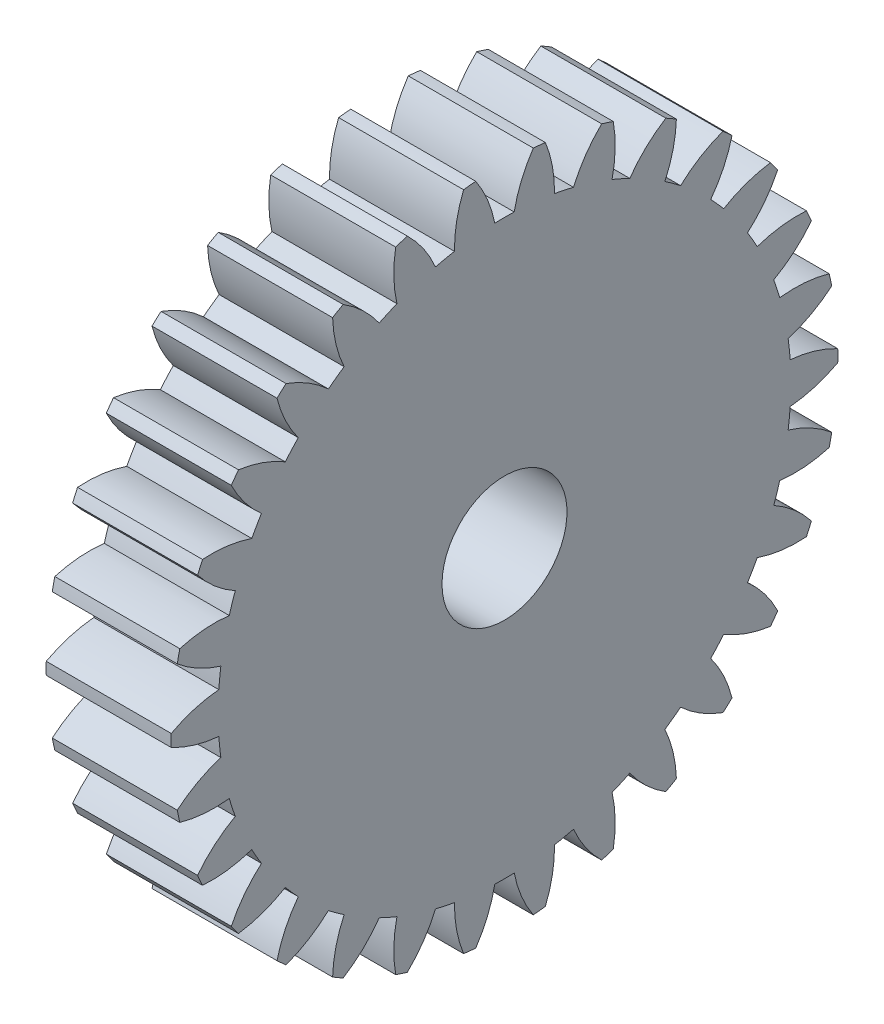
SolidWorks part; units mm, degrees
ref_plane "Plane1" through (0, 0, 0) normal (0, 0, 1) x (1, 0, 0)
ref_plane "Plane2" through (0, 0, 0) normal (0, 1, 0) x (1, 0, 0)
ref_plane "Plane3" through (0, 0, 0) normal (1, 0, 0) x (0, 0, -1)
sketch "HoldingSke" plane through (0, 0, 0) normal (0, 1, 0) x (1, 0, 0)
  line L0 (0, 0) -> (1.7321, -1)
  line L1 (-15, 0) -> (100, 0) construction
  line L2 (0, 0) -> (-2.1039, 2.3779)
  line L3 (0, 0) -> (-11.863, 4.5341)
  line L4 (0, 0) -> (7.479, 4.318)
  line L5 (0, 0) -> (-46.8476, -17.4728)
  line L6 (0, 0) -> (-2.4869, -1.6779)
  line L7 (-2.1039, 2.3779) -> (8.6586, 51.2059)
  line L8 (-76.2, 54.61) -> (-75.7, 54.61)
  line L9 (-71.009, 38.7566) -> (-53.1078, 45.2721)
  line L10 (-76.2, 71.12) -> (104.1128, 71.12)
  line L11 (0, 0) -> (-3, 0)
  line L12 (-76.2, 101.6) -> (-76.181, 101.6)
  line L13 (24.9733, 27.94) -> (52.9518, 28.4284)
  line L14 (24.9733, 27.94) -> (24.9743, 27.94)
  line L15 (24.9733, 27.94) -> (100.4006, 29.5858)
  line L16 (-63.627, -0.5) -> (-12.827, -0.5)
  circle A0 centre (0, 0) radius 1.5
  circle A1 centre (0, 0) radius 6.874
  circle A2 centre (0, 0) radius 37.5
  circle A3 centre (0, 0) radius 1.5
  dimension "MHD" = 13.748
  dimension "Hub_dia" = 75
  dimension "Bore" = 3
  dimension "MBD" = 3
  dimension "Num_teeth" = 30
  dimension "Pitch" = 2
  dimension "Overall_len" = 50
  dimension "Show_teeth" = 30
  dimension "Thickness" = 3
  dimension "OAL" = 50.0001
  dimension "T_dim" = 0.5
  dimension "Ap" = 20
  dimension "H" = 19.05
  dimension "Pitch_radius" = 180.3128
  dimension "Width" = 3
  dimension "Backlash" = 0.019
  dimension "Addendum_fac" = 1
  dimension "Dedendum_fac" = 1.25
  dimension "Clearance_fac" = 0.25
  dimension "Dedendum_add" = 0.001
  dimension "Module" = 0.5
sketch "BasProSke" plane through (0, 0, 0) normal (0, 1, 0) x (1, 0, 0)
  line L0 (-10, 0) -> (60, 0) construction
  line L1 (0, 0) -> (0, 8)
  line L2 (0, 0) -> (3, 0)
  line L3 (3, 0) -> (3, 8)
  line L4 (3, 8) -> (0, 8)
  dimension "Thickness" = 3
  dimension "Diameter" = 16
revolve "Base-Revolve" add sketch "BasProSke" angle 360 about L0
sketch "TooCutSke" plane through (0, 0, 0) normal (1, 0, 0) x (0, 0, -1)
  line L1 (0, 0) -> (0, 107) construction
  line L2 (0, 0) -> (-0.4258, 7.4879) construction
  line L3 (0, 0) -> (-1.5661, 14.9007) construction
  line L4 (-0.4258, 7.4879) -> (-0.7831, 7.4504) construction
  arc A0 (0.2331, 6.87) -> (-0.2331, 6.87) centre (0, 0) ccw
  arc A1 (0.707, 7.9942) -> (-0.707, 7.9942) centre (0, 0) ccw
  circle A2 centre (0, 0) radius 7.5 construction
  circle A3 centre (0, 0) radius 7.0477 construction
  arc A4 (-0.2331, 6.87) -> (-0.707, 7.9942) centre (-3.1767, 6.2911) ccw
  arc A5 (0.707, 7.9942) -> (0.2331, 6.87) centre (3.1767, 6.2911) ccw
  dimension "Root_dia" = 13.748
  dimension "Overcut_dia" = 16.0508
  dimension "Pitch_dia" = 15
  dimension "Base_dia" = 14.0954
  dimension "Flank_rad" = 3
  dimension "Half_ang" = 6
  dimension "Half_CT" = 0.3593
extrude "ToothCut" cut sketch "TooCutSke" along normal through all
fillet "Breaks" [suppressed] radius 0.01
fillet "RootFillets" [suppressed] radius 0.126
pattern_circular "TeethCuts" count 30 every 12 about axis through (-10, 0, 0) along (1, 0, 0) of "ToothCut", "RootFillets", "Breaks"
sketch "HubNeaOneSke" plane through (0, 0, 0) normal (-1, 0, 0) x (0, 0, 1)
  circle A0 centre (0, 0) radius 6.874
  dimension "Diameter" = 13.748
extrude "HubNearOne" [suppressed] add sketch "HubNeaOneSke" along normal blind 47.0001
sketch "HubNeaBotSke" plane through (0, 0, 0) normal (-1, 0, 0) x (0, 0, 1)
  circle A0 centre (0, 0) radius 6.874
  dimension "Diameter" = 13.748
extrude "HubNearBoth" [suppressed] add sketch "HubNeaBotSke" along normal blind 23.5
ref_plane "FarPln" through (3, 0, 0) normal (1, 0, 0) x (0, 0, -1)
sketch "HubFarSke" plane through (3, 0, 0) normal (1, 0, 0) x (0, 0, -1)
  circle A0 centre (0, 0) radius 6.874
  dimension "Diameter" = 13.748
extrude "HubFar" [suppressed] add sketch "HubFarSke" along normal blind 23.5
sketch "BorSke" plane through (0, 0, 0) normal (1, 0, 0) x (0, 0, -1)
  circle A0 centre (0, 0) radius 1.5
  dimension "Diameter" = 3
extrude "Bore" cut sketch "BorSke" along normal mid plane 100.0001
sketch "KeySke" plane through (0, 0, 0) normal (1, 0, 0) x (0, 0, -1)
  line L0 (-0.6, 0) -> (-0.6, 2)
  line L1 (-0.6, 2) -> (0.6, 2)
  line L2 (0.6, 2) -> (0.6, 0)
  line L3 (0, 0) -> (0, 34) construction
  line L4 (-0.6, 0) -> (0.6, 0)
  dimension "Offset" = 2
  dimension "Width" = 1.2
extrude "Keyway" [suppressed] cut sketch "KeySke" along normal mid plane 100.0001
pattern_circular "Keyway2" [suppressed] count 2 every 90 about axis through (-10, 0, 0) along (1, 0, 0)
equation "' \"Module@HoldingSke\" = 6.35"
equation "' \"Num_teeth@HoldingSke\" = 12"
equation "' \"Ap@HoldingSke\" =  20"
equation "' \"Ap@HoldingSke\" = 20"
equation "' \"Width@HoldingSke\" = 0.5 * 25.4"
equation "' \"Hub_dia@HoldingSke\"= 1 * 25.4"
equation "' \"Hub_dia@HoldingSke\" = 1 * 25.4"
equation "' \"Overall_len@HoldingSke\" = 1.0 * 25.4"
equation "' \"Bore@HoldingSke\" = 0.75 * 25.4"
equation "' \"T_dim@HoldingSke\" = 0.1 * 25.4"
equation "' \"Width@KeySke\" = 0.25 * 25.4"
equation "' \"Show_teeth@HoldingSke\" = 13"
equation "' \"Backlash@HoldingSke\" = 0.009 * 25.4"
equation "' \"Addendum_fac@HoldingSke\" = 1.0"
equation "' \"Dedendum_fac@HoldingSke\" = 1.25"
equation "' \"Dedendum_add@HoldingSke\" = 0.00005 * 25.4"
equation "' \"Clearance_fac@HoldingSke\" = 0.25"
equation "\"Pitch@HoldingSke\" = 1 / \"Module@HoldingSke\""
equation "\"Overcut_dia@TooCutSke\" = (\"Num_teeth@HoldingSke\" + 2 * \"Addendum_fac@HoldingSke\") / \"Pitch@HoldingSke\" + 0.002 * 25.4"
equation "\"Pitch_dia@TooCutSke\" = \"Num_teeth@HoldingSke\" / \"Pitch@HoldingSke\""
equation "\"Base_dia@TooCutSke\" = \"Num_teeth@HoldingSke\" / \"Pitch@HoldingSke\" * cos((\"Ap@HoldingSke\"  * 3.14159265 / 180))"
equation "\"Root_dia@TooCutSke\" = (\"Num_teeth@HoldingSke\" + 2) / \"Pitch@HoldingSke\" - 2 * (\"Addendum_fac@HoldingSke\" + \"Dedendum_fac@HoldingSke\") / \"Pitch@HoldingSke\" - \"Dedendum_add@HoldingSke\" * 2"
equation "\"Half_ang@TooCutSke\" = 180 / \"Num_teeth@HoldingSke\""
equation "\"Half_CT@TooCutSke\" = \"Num_teeth@HoldingSke\" / \"Pitch@HoldingSke\" * sin((3.14159265 / 2 / \"Num_teeth@HoldingSke\")) / 2 - 7 * \"Backlash@HoldingSke\" / 4"
equation "\"Flank_rad@TooCutSke\" = \"Num_teeth@HoldingSke\" / \"Pitch@HoldingSke\" / 5"
equation "\"Radius@RootFillets\" = \"Clearance_fac@HoldingSke\" / \"Pitch@HoldingSke\" + \"Dedendum_add@HoldingSke\""
equation "\"Break_rad@Breaks\" = 0.02 / \"Pitch@HoldingSke\""
equation "\"Thickness@HoldingSke\" = \"Width@HoldingSke\""
equation "\"OAL@HoldingSke\" = \"Thickness@HoldingSke\""
equation "\"MHD@HoldingSke\" = (\"Num_teeth@HoldingSke\" + 2) / \"Pitch@HoldingSke\" - 2 * (\"Addendum_fac@HoldingSke\" + \"Dedendum_fac@HoldingSke\")  / \"Pitch@HoldingSke\" - \"Dedendum_add@HoldingSke\" * 2"
equation "\"MBD@HoldingSke\" = (\"Num_teeth@HoldingSke\" + 2) / \"Pitch@HoldingSke\" - 2 * (\"Addendum_fac@HoldingSke\" + \"Dedendum_fac@HoldingSke\")  / \"Pitch@HoldingSke\" - \"Dedendum_add@HoldingSke\" * 2 - 0.002 * 25.4"
equation "\"MHD@HoldingSke\" = ((sgn( \"MHD@HoldingSke\" - \"Hub_dia@HoldingSke\" )-1)*( \"MHD@HoldingSke\" - \"Hub_dia@HoldingSke\" ))/-2+ \"Hub_dia@HoldingSke\""
equation "\"MBD@HoldingSke\" = ((sgn( \"MBD@HoldingSke\" - \"Bore@HoldingSke\" )-1)*( \"MBD@HoldingSke\" - \"Bore@HoldingSke\" ))/-2+ \"Bore@HoldingSke\""
equation "\"OAL@HoldingSke\" = ((sgn( \"OAL@HoldingSke\" - \"Overall_len@HoldingSke\" )+1)*( \"OAL@HoldingSke\" - \"Overall_len@HoldingSke\" ))/2 + \"Overall_len@HoldingSke\" + 0.000002 * 25.4"
equation "\"Num_teeth@TeethCuts\" = int( \"Show_teeth@HoldingSke\" ) + 1"
equation "\"Num_teeth@TeethCuts\" = ((sgn( \"Num_teeth@TeethCuts\" - \"Num_teeth@HoldingSke\" )-1)*( \"Num_teeth@TeethCuts\" - \"Num_teeth@HoldingSke\" ))/-2+ \"Num_teeth@HoldingSke\""
equation "\"Num_teeth@TeethCuts\" = ((sgn( \"Num_teeth@TeethCuts\" - 2.0)+1)*( \"Num_teeth@TeethCuts\" - 2.0))/2 +2.0"
equation "\"Angle@TeethCuts\" = 360.0 / \"Num_teeth@HoldingSke\""
equation "\"Diameter@BasProSke\" = (\"Num_teeth@HoldingSke\" + 2 * \"Addendum_fac@HoldingSke\") / \"Pitch@HoldingSke\""
equation "\"Thickness@BasProSke\"  = \"Thickness@HoldingSke\""
equation "' \"Fillet_rad@BasProSke\" =  \"Thickness@HoldingSke\" * 0.05"
equation "' \"Fillet_rad@BasProSke\" = \"Thickness@HoldingSke\" * 0.05"
equation "\"MHD@HoldingSke\" = ((sgn( \"MHD@HoldingSke\" - \"Root_dia@TooCutSke\" )-1)*( \"MHD@HoldingSke\" - \"Root_dia@TooCutSke\" ))/-2+ \"Root_dia@TooCutSke\""
equation "\"Diameter@HubNeaOneSke\" = \"MHD@HoldingSke\""
equation "\"Length@HubNearOne\" = \"OAL@HoldingSke\" - \"Thickness@BasProSke\""
equation "\"Diameter@HubNeaBotSke\" = \"MHD@HoldingSke\""
equation "\"Length@HubNearBoth\" = ( \"OAL@HoldingSke\" - \"Thickness@BasProSke\" ) / 2.0"
equation "\"Thickness@FarPln\" = \"Thickness@BasProSke\""
equation "\"Diameter@HubFarSke\" = \"MHD@HoldingSke\""
equation "\"Length@HubFar\" = ( \"OAL@HoldingSke\" - \"Thickness@BasProSke\" ) / 2.0"
equation "\"Diameter@BorSke\" = \"MBD@HoldingSke\""
equation "\"D1@Bore\" = \"OAL@HoldingSke\" * 2.0"
equation "\"D1@Keyway\" = \"OAL@HoldingSke\" * 2.0"
equation "\"Offset@KeySke\" = \"T_dim@HoldingSke\" + \"MBD@HoldingSke\" / 2.0"
